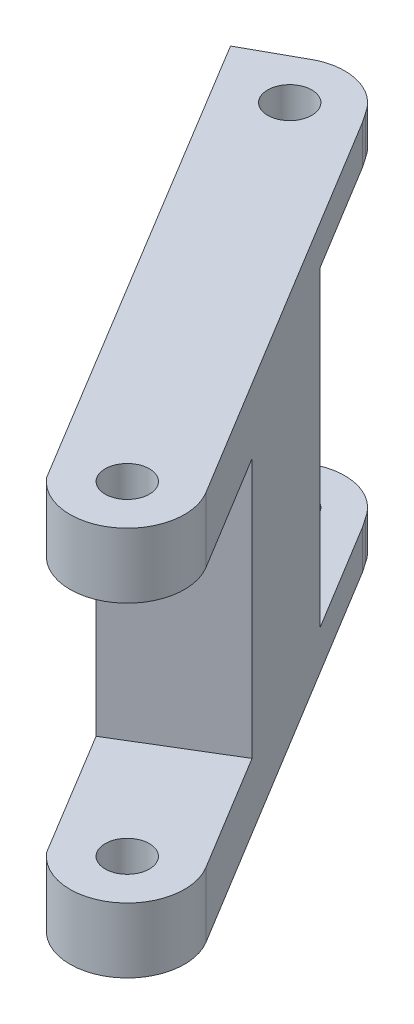
SolidWorks part; units mm, degrees
ref_plane "Front Plane" through (0, 0, 0) normal (0, 0, 1) x (1, 0, 0)
ref_plane "Top Plane" through (0, 0, 0) normal (0, 1, 0) x (1, 0, 0)
ref_plane "Right Plane" through (0, 0, 0) normal (1, 0, 0) x (0, 0, -1)
sketch "Sketch1" plane through (0, 0, 0) normal (0, 1, 0) x (1, 0, 0)
  line L0 (47.2297, 219.0186) -> (732.563, 219.0186) construction
  line L1 (-9.1686, 46.1676) -> (12.5392, 10.2937)
  line L2 (19.6719, 15.4374) -> (1.0019, 46.1676)
  line L3 (-5.3139, 48.2966) -> (-9.1686, 46.1676)
  line L4 (1.0019, 46.1676) -> (0.516, 46.8734)
  arc A0 (11.8141, 11.4919) -> (19.6719, 15.4374) centre (15.9024, 13.1473) ccw
  arc A1 (0.516, 46.8734) -> (-5.3139, 48.2966) centre (-3.1106, 44.6701) ccw
  circle A2 centre (-3.1106, 44.6701) radius 1.7
  circle A3 centre (15.9024, 13.1473) radius 1.7
extrude "Boss-Extrude3" add sketch "Sketch1" along normal blind 30 contours L4 A1 L3 L1 A0 L2 A3 A2
sketch "Sketch3" plane through (13.7378, 0, -8.3129) normal (-0.8556, 0, 0.5177) x (0.5177, 0, 0.8556)
  line L0 (-44.2457, 30) -> (-44.2457, 0) construction
  line L1 (-44.2457, 3) -> (-29.2457, 3)
  line L2 (-44.2457, 3) -> (-44.2457, 27)
  line L3 (-44.2457, 27) -> (-29.2457, 27)
  line L4 (-29.2457, 3) -> (-29.2457, 27)
  line L5 (-44.2457, 0) -> (-2.3152, 0) construction
  line L6 (-44.2457, 30) -> (-2.3152, 30) construction
  line L8 (-13.6048, 5) -> (1.3952, 5)
  line L9 (-13.6048, 5) -> (-13.6048, 25)
  line L10 (-13.6048, 25) -> (1.3952, 25)
  line L11 (1.3952, 5) -> (1.3952, 25)
  line L12 (1.3952, 0) -> (1.3952, 30) construction
  dimension "D1" = 3
  dimension "D2" = 3
  dimension "D3" = 15
  dimension "D4" = 5
  dimension "D5" = 5
  dimension "D6" = 15
  dimension "D7" = 0
extrude "Cut-Extrude1" cut sketch "Sketch3" against normal blind 30
